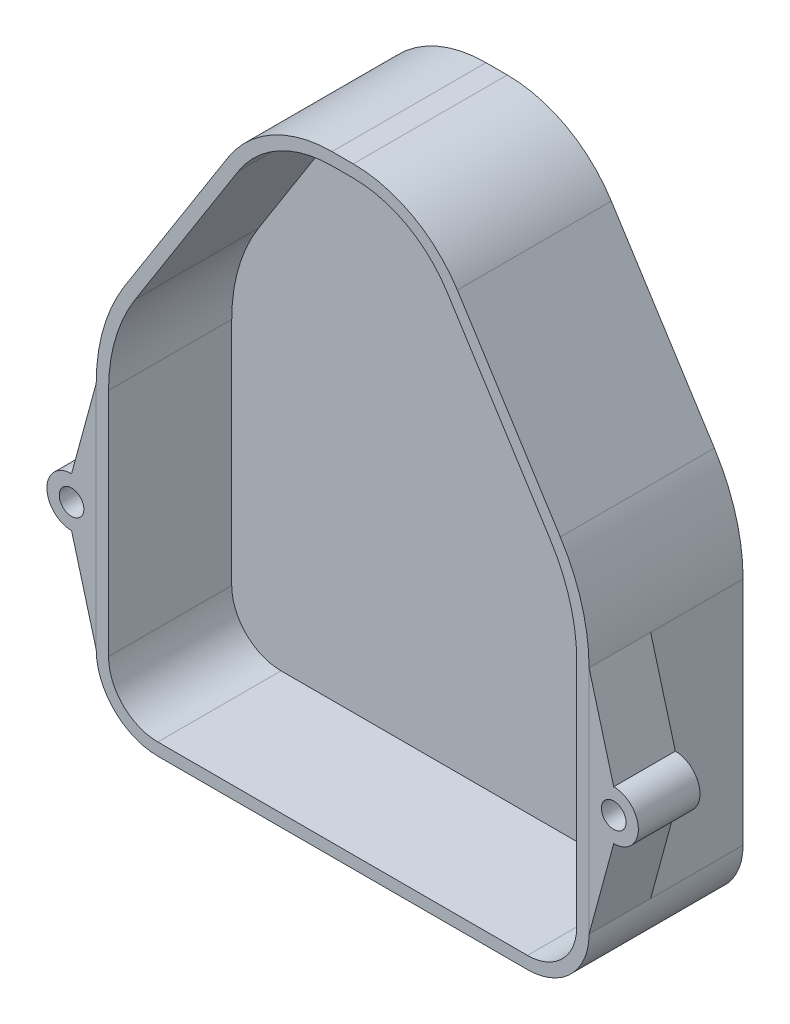
SolidWorks part; units mm, degrees
ref_plane "Front Plane" through (0, 0, 0) normal (0, 0, 1) x (1, 0, 0)
ref_plane "Top Plane" through (0, 0, 0) normal (0, 1, 0) x (1, 0, 0)
ref_plane "Right Plane" through (0, 0, 0) normal (1, 0, 0) x (0, 0, -1)
sketch "Sketch2" plane through (0, 0, 0) normal (0, 0, 1) x (1, 0, 0)
  line L4 (-40, -37) -> (-40, 0.4106)
  line L5 (-40, 9.1226) -> (40, 9.1226) construction
  line L11 (-30, -47) -> (0, -47)
  line L12 (0, 0) -> (0, 52.1226) construction
  line L13 (0, 52.1226) -> (-1.7274, 52.1226)
  line L15 (-18.6164, 42.8352) -> (-35.3336, 16.4795)
  line L16 (0, 50.1226) -> (-1.7274, 50.1226)
  line L17 (-16.9275, 41.7639) -> (-33.6447, 15.4082)
  line L18 (-38, -37) -> (-38, 0.4106)
  line L19 (-30, -45) -> (0, -45)
  line L21 (30, -45) -> (0, -45)
  line L22 (38, -37) -> (38, 0.4106)
  line L23 (16.9275, 41.7639) -> (33.6447, 15.4082)
  line L24 (0, 50.1226) -> (1.7274, 50.1226)
  line L25 (18.6164, 42.8352) -> (35.3336, 16.4795)
  line L26 (0, 52.1226) -> (1.7274, 52.1226)
  line L27 (30, -47) -> (0, -47)
  line L28 (40, -37) -> (40, 0.4106)
  arc A1 (-40, -37) -> (-30, -47) centre (-30, -37) ccw
  arc A4 (-1.7274, 52.1226) -> (-18.6164, 42.8352) centre (-1.7274, 32.1226) ccw
  arc A5 (-40, 0.4106) -> (-35.3336, 16.4795) centre (-10, 0.4106) cw
  arc A6 (-1.7274, 50.1226) -> (-16.9275, 41.7639) centre (-1.7274, 32.1226) ccw
  arc A7 (-38, 0.4106) -> (-33.6447, 15.4082) centre (-10, 0.4106) cw
  arc A8 (-38, -37) -> (-30, -45) centre (-30, -37) ccw
  arc A9 (38, -37) -> (30, -45) centre (30, -37) cw
  arc A10 (38, 0.4106) -> (33.6447, 15.4082) centre (10, 0.4106) ccw
  arc A11 (1.7274, 50.1226) -> (16.9275, 41.7639) centre (1.7274, 32.1226) cw
  arc A12 (40, 0.4106) -> (35.3336, 16.4795) centre (10, 0.4106) ccw
  arc A13 (1.7274, 52.1226) -> (18.6164, 42.8352) centre (1.7274, 32.1226) cw
  arc A14 (40, -37) -> (30, -47) centre (30, -37) cw
  point P0 (0, 0)
  point P12 (0, -47)
  point P29 (0, 9.1226)
  dimension "D4" = 30
  dimension "D3" = 20
  dimension "D5" = 30
  dimension "D6" = 10
  dimension "D1" = 40
  dimension "D2" = 9.1226
  dimension "D7" = 2
  dimension "D8" = 47
  dimension "D9" = 43
extrude "Boss-Extrude4" add sketch "Sketch2" along normal blind 25
sketch "Sketch4" plane through (0, 0, 25) normal (0, 0, 1) x (1, 0, 0)
  line L0 (0, 0) -> (0, -18.2947) construction
  line L5 (40, -37) -> (40, 0.4106) construction
  line L6 (44, -18.2947) -> (-54.4507, -18.2947) construction
  line L7 (-40, 0.4106) -> (-40, -37) construction
  line L8 (40, 0.4106) -> (44, -14.2947)
  line L9 (40, -37) -> (44, -22.2947)
  line L10 (-40, 0.4106) -> (-44, -14.2947)
  line L11 (-44, -22.2947) -> (-40, -37)
  line L12 (-40, 0.4106) -> (-40, -37)
  line L13 (40, 0.4106) -> (40, -37)
  circle A2 centre (44, -18.2947) radius 2
  arc A3 (44, -22.2947) -> (44, -14.2947) centre (44, -18.2947) ccw
  circle A4 centre (-44, -18.2947) radius 2
  arc A5 (-44, -14.2947) -> (-44, -22.2947) centre (-44, -18.2947) ccw
  dimension "D3" = 4
  dimension "D4" = 8
  dimension "D6" = 4
  dimension "D7" = 8
  dimension "D5" = 4
  dimension "D8" = 4
extrude "Boss-Extrude5" add sketch "Sketch4" against normal blind 10 separate body
ref_plane "Plane1" through (0, 0, 12.5) normal (0, 0, -1) x (-1, 0, 0)
sketch "Sketch6" plane through (0, 0, 0) normal (0, 0, -1) x (-1, 0, 0)
  line L6 (1.7274, 52.1226) -> (-1.7274, 52.1226)
  line L7 (-18.6164, 42.8352) -> (-35.3336, 16.4795)
  line L8 (-40, 0.4106) -> (-40, -37)
  line L9 (-30, -47) -> (30, -47)
  line L10 (40, -37) -> (40, 0.4106)
  line L11 (35.3336, 16.4795) -> (18.6164, 42.8352)
  line L12 (1.7274, 52.1226) -> (-1.7274, 52.1226)
  line L13 (-18.6164, 42.8352) -> (-35.3336, 16.4795)
  line L14 (-40, 0.4106) -> (-40, -37)
  line L15 (-30, -47) -> (30, -47)
  line L16 (40, -37) -> (40, 0.4106)
  line L17 (35.3336, 16.4795) -> (18.6164, 42.8352)
  arc A6 (18.6164, 42.8352) -> (1.7274, 52.1226) centre (1.7274, 32.1226) ccw
  arc A7 (-1.7274, 52.1226) -> (-18.6164, 42.8352) centre (-1.7274, 32.1226) ccw
  arc A8 (-35.3336, 16.4795) -> (-40, 0.4106) centre (-10, 0.4106) ccw
  arc A9 (-40, -37) -> (-30, -47) centre (-30, -37) ccw
  arc A10 (30, -47) -> (40, -37) centre (30, -37) ccw
  arc A11 (40, 0.4106) -> (35.3336, 16.4795) centre (10, 0.4106) ccw
  arc A12 (18.6164, 42.8352) -> (1.7274, 52.1226) centre (1.7274, 32.1226) ccw
  arc A13 (-1.7274, 52.1226) -> (-18.6164, 42.8352) centre (-1.7274, 32.1226) ccw
  arc A14 (-35.3336, 16.4795) -> (-40, 0.4106) centre (-10, 0.4106) ccw
  arc A15 (-40, -37) -> (-30, -47) centre (-30, -37) ccw
  arc A16 (30, -47) -> (40, -37) centre (30, -37) ccw
  arc A17 (40, 0.4106) -> (35.3336, 16.4795) centre (10, 0.4106) ccw
  dimension "D1" = 0
extrude "Boss-Extrude7" add sketch "Sketch6" against normal blind 5
